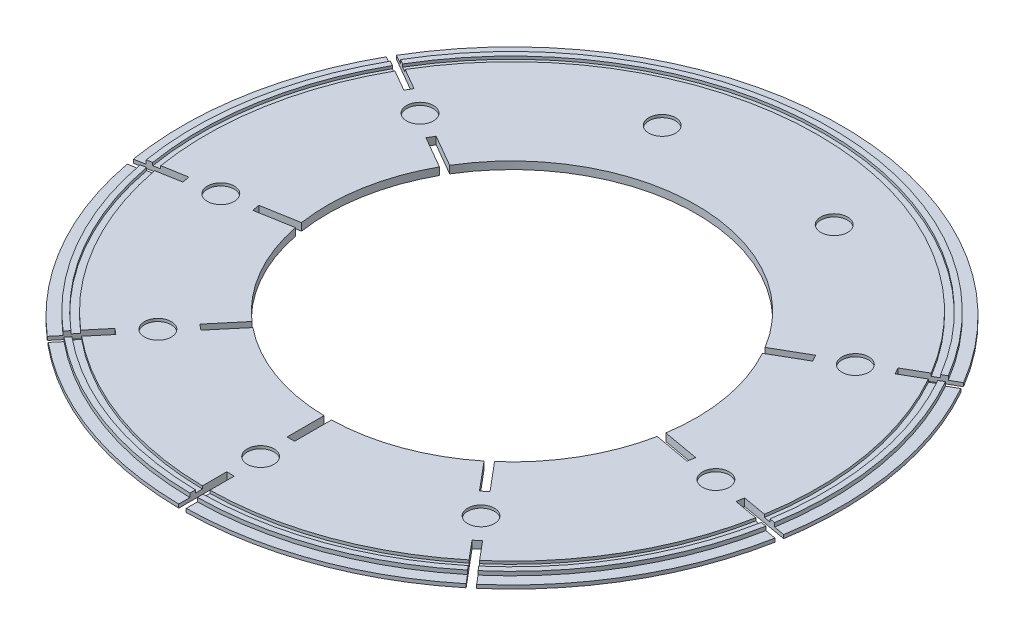
SolidWorks part; units mm, degrees
material "Balsa"
ref_plane "Front Plane" through (0, 0, 0) normal (0, 0, 1) x (1, 0, 0)
ref_plane "Top Plane" through (0, 0, 0) normal (0, 1, 0) x (1, 0, 0)
ref_plane "Right Plane" through (0, 0, 0) normal (1, 0, 0) x (0, 0, -1)
sketch "Sketch1" plane through (0, 0, 0) normal (0, 1, 0) x (1, 0, 0)
  circle A0 centre (0, 0) radius 295
  circle A1 centre (0, 0) radius 165
  dimension "D1" = 295
  dimension "D2" = 165
extrude "Boss-Extrude1" add sketch "Sketch1" along normal blind 6.7 contours A0
sketch "Sketch2" plane through (0, 6.7, 0) normal (0, 1, 0) x (1, 0, 0)
  line L0 (0, 0) -> (255.4775, 147.5) construction
  line L1 (216.5634, 128.9012) -> (219.9134, 123.0988)
  line L2 (140.3532, 84.9012) -> (169.798, 101.9012)
  line L3 (140.3532, 84.9012) -> (143.7032, 79.0988)
  line L4 (143.7032, 79.0988) -> (173.148, 96.0988)
  line L5 (169.798, 101.9012) -> (173.148, 96.0988)
  line L6 (254.6685, 150.9012) -> (258.0185, 145.0988)
  line L7 (258.0185, 145.0988) -> (219.9134, 123.0988)
  line L8 (254.6685, 150.9012) -> (216.5634, 128.9012)
  line L9 (107.9834, -123.478) -> (129.8382, -149.5235)
  line L10 (107.9834, -123.478) -> (102.8509, -127.7846)
  line L11 (102.8509, -127.7846) -> (124.7057, -153.8301)
  line L12 (129.8382, -149.5235) -> (124.7057, -153.8301)
  line L13 (292.0848, -48.1008) -> (248.7533, -40.4602)
  line L14 (292.0848, -48.1008) -> (290.9214, -54.699)
  line L15 (290.9214, -54.699) -> (247.5898, -47.0584)
  line L16 (162.0902, -25.1792) -> (195.5737, -31.0832)
  line L17 (162.0902, -25.1792) -> (160.9268, -31.7774)
  line L18 (160.9268, -31.7774) -> (194.4102, -37.6814)
  line L19 (195.5737, -31.0832) -> (194.4102, -37.6814)
  line L20 (248.7533, -40.4602) -> (247.5898, -47.0584)
  line L21 (192.8314, -224.5958) -> (164.5487, -190.8899)
  line L22 (192.8314, -224.5958) -> (187.6989, -228.9025)
  line L23 (0, 0) -> (189.6223, -225.9831) construction
  line L24 (187.6989, -228.9025) -> (159.4162, -195.1965)
  line L25 (3.35, -164) -> (3.35, -198)
  line L26 (3.35, -164) -> (-3.35, -164)
  line L27 (164.5487, -190.8899) -> (159.4162, -195.1965)
  line L28 (3.35, -296) -> (3.35, -252)
  line L29 (0, 0) -> (290.5183, -51.2262) construction
  line L30 (-3.35, -164) -> (-3.35, -198)
  line L31 (3.35, -198) -> (-3.35, -198)
  line L32 (3.35, -296) -> (-3.35, -296)
  line L33 (-3.35, -296) -> (-3.35, -252)
  line L34 (0, 0) -> (0, -295) construction
  line L35 (3.35, -252) -> (-3.35, -252)
  line L36 (-102.8509, -127.7846) -> (-124.7057, -153.8301)
  line L37 (-102.8509, -127.7846) -> (-107.9834, -123.478)
  line L38 (-107.9834, -123.478) -> (-129.8382, -149.5235)
  line L39 (-124.7057, -153.8301) -> (-129.8382, -149.5235)
  line L40 (-187.6989, -228.9025) -> (-159.4162, -195.1965)
  line L41 (-187.6989, -228.9025) -> (-192.8314, -224.5958)
  line L42 (0, 0) -> (-189.6223, -225.9831) construction
  line L43 (-192.8314, -224.5958) -> (-164.5487, -190.8899)
  line L44 (-160.9268, -31.7774) -> (-194.4102, -37.6814)
  line L45 (-160.9268, -31.7774) -> (-162.0902, -25.1792)
  line L46 (-162.0902, -25.1792) -> (-195.5737, -31.0832)
  line L47 (-194.4102, -37.6814) -> (-195.5737, -31.0832)
  line L48 (-159.4162, -195.1965) -> (-164.5487, -190.8899)
  line L49 (-290.9214, -54.699) -> (-247.5898, -47.0584)
  line L50 (0, 0) -> (-290.5183, -51.2262) construction
  line L51 (-290.9214, -54.699) -> (-292.0848, -48.1008)
  line L52 (-292.0848, -48.1008) -> (-248.7533, -40.4602)
  line L53 (-247.5898, -47.0584) -> (-248.7533, -40.4602)
  line L54 (-258.0185, 145.0988) -> (-219.9134, 123.0988)
  line L55 (-143.7032, 79.0988) -> (-173.148, 96.0988)
  line L56 (-143.7032, 79.0988) -> (-140.3532, 84.9012)
  line L57 (-140.3532, 84.9012) -> (-169.798, 101.9012)
  line L58 (-173.148, 96.0988) -> (-169.798, 101.9012)
  line L59 (-258.0185, 145.0988) -> (-254.6685, 150.9012)
  line L60 (-254.6685, 150.9012) -> (-216.5634, 128.9012)
  line L61 (0, 0) -> (-255.4775, 147.5) construction
  line L62 (-219.9134, 123.0988) -> (-216.5634, 128.9012)
  line L63 (0, 0) -> (0, 102.8222) construction
  circle A0 centre (0, 0) radius 295 construction
  point P13 (-12.0777, 27.2748)
  point P75 (142.0282, 82)
  dimension "D1" = 34
  dimension "D2" = 6.7
  dimension "D3" = 3.35
  dimension "D6" = 40
  dimension "D4" = 164
  dimension "D5" = 54
  dimension "D8" = 44
  dimension "D7" = 7
extrude "Cut-Extrude3" cut sketch "Sketch2" against normal blind 6.7
sketch "Sketch3" plane through (0, 6.7, 0) normal (0, 1, 0) x (1, 0, 0)
  line L0 (3.35, -198) -> (-3.35, -198) construction
  circle A1 centre (0, 0) radius 280
  circle A2 centre (0, 0) radius 273.8
  circle A3 centre (0, -225) radius 12
  circle A4 centre (-144.6272, -172.36) radius 12
  arc A6 (291.0813, -47.9238) -> (257.136, 144.5893) centre (0, 0) ccw construction
  circle A7 centre (-221.5817, -39.0708) radius 12
  circle A8 centre (-194.8557, 112.5) radius 12
  circle A9 centre (-76.9545, 211.4308) radius 12
  circle A10 centre (76.9545, 211.4308) radius 12
  circle A11 centre (194.8557, 112.5) radius 12
  circle A12 centre (221.5817, -39.0708) radius 12
  circle A13 centre (144.6272, -172.36) radius 12
  point P13 (0, -198)
  point P30 (0, 0)
  dimension "D5" = 24
  dimension "D2" = 6.2
  dimension "D7" = 27
  dimension "D1" = 15
  dimension "D6" = 9
extrude "Cut-Extrude4" cut sketch "Sketch3" against normal blind 2.5 contours A1 | A2 | A3 | A4 | A7 | A8 | A13 | A12 | A11 | A9 | A10
sketch "Sketch5" plane through (0, 6.7, 0) normal (0, 1, 0) x (1, 0, 0)
  circle A0 centre (0, 0) radius 285
  circle A1 centre (0, 0) radius 296
  arc A3 (291.0813, -47.9238) -> (257.136, 144.5893) centre (0, 0) ccw construction
  dimension "D1" = 10
  dimension "D2" = 1
extrude "Cut-Extrude5" cut sketch "Sketch5" against normal blind 3.5
equation "\"Ring inner radius\"= 80mm"
equation "\"D1@Sketch1\" = \"BottomRing outer radius\""
equation "\"Heart cable hole radius\"= 3.5mm"
equation "\"Dogbone radius\"= 3mm"
equation "\"Tree side stock thickness\"= 6.7mm"
equation "\"D2@Sketch2\"= \"Tree side stock thickness\""
equation "\"D3@Sketch2\"= \"Tree side stock thickness\" / 2"
equation "\"Ring stock thickness\"= 6.7mm"
equation "\"D1@Boss-Extrude1\"= \"Ring stock thickness\""
equation "\"D1@Cut-Extrude3\"= \"Ring stock thickness\""
equation "\"Tree teeth\"= 15mm"
equation "\"Tree slot\"= 15mm"
equation "\"D1@Sketch2\"=\"BottomRing inner slot\" + \"Cut-Extrude Tolerance\" + \"Dogbone radius\""
equation "\"Bottom ring outer radius\"= \"Ring inner radius\" + \"Tree teeth\""
equation "\"D4@Sketch2\"= \"BottomRing inner radius\" - \"Cut-Extrude Tolerance\""
equation "\"Cut-Extrude Tolerance\"= 1mm"
equation "\"Ring outer radius\"= \"Ring inner radius\" + \"Tree slot\" + 10"
equation "\"D2@Sketch1\" = \"BottomRing inner radius\""
equation "\"Tree bottom teeth\"= 20mm"
equation "\"Top-bottom rings offset\"= 80mm"
equation "\"BottomRing layers overlap\"= 10mm"
equation "\"BottomRing inner radius\"= \"Ring inner radius\" - \"Tree teeth\" + \"Top-bottom rings offset\" + 20"
equation "\"BottomRing outer radius\"= \"BottomRing inner radius\" + \"BottomRing inner slot\" + \"BottomRing outer slot\" + \"BottomRing intersection\""
equation "\"BottomRing inner slot\"= 30mm"
equation "\"BottomRing outer slot\"= 40mm"
equation "\"BottomRing intersection\"= 60mm"
equation "\"D5@Sketch2\"= \"BottomRing intersection with dogbones\""
equation "\"D8@Sketch2\"= \"BottomRing outer slot\"+\"Dogbone radius\"+\"Cut-Extrude Tolerance\""
equation "\"BottomRing intersection with dogbones\"= \"BottomRing intersection\" - 2 * \"Dogbone radius\""
equation "\"D7@Sketch3\"=\"BottomRing intersection with dogbones\" / 2"
equation "\"D2@Sketch5\"=\"Cut-Extrude Tolerance\""
